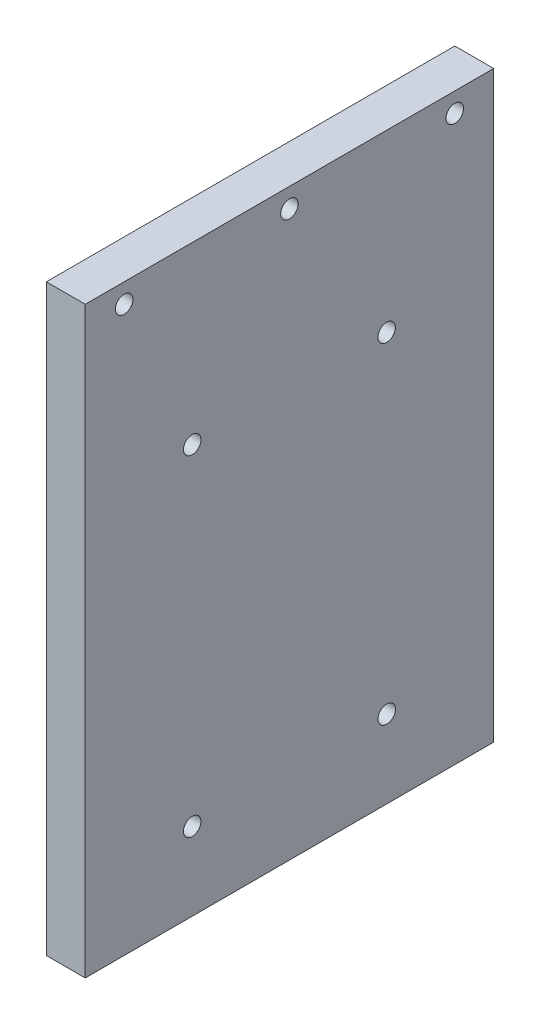
SolidWorks part; units mm, degrees
material "ABS"
ref_plane "Alzado" through (0, 0, 0) normal (0, 0, 1) x (1, 0, 0)
ref_plane "Planta" through (0, 0, 0) normal (0, 1, 0) x (1, 0, 0)
ref_plane "Vista lateral" through (0, 0, 0) normal (1, 0, 0) x (0, 0, -1)
sketch "Croquis1" plane through (0, 0, 0) normal (1, 0, 0) x (0, 0, -1)
  line L1 (-52.5, -75) -> (52.5, -75)
  line L2 (-52.5, -75) -> (-52.5, 75)
  line L3 (-52.5, 75) -> (52.5, 75)
  line L4 (52.5, -75) -> (52.5, 75)
  line L5 (-52.5, -75) -> (52.5, 75) construction
  line L6 (-52.5, 75) -> (52.5, -75) construction
  point P0 (0, 0)
  dimension "D1" = 105
  dimension "D2" = 150
extrude "Saliente-Extruir1" add sketch "Croquis1" along normal blind 10
sketch "Croquis2" plane through (10, 0, 0) normal (1, 0, 0) x (0, 0, -1)
  line L0 (0, 75) -> (0, 70) construction
  line L1 (52.5, 75) -> (-52.5, 75) construction
  line L2 (42.5, 70) -> (-42.5, 70) construction
  line L3 (-52.5, 75) -> (-52.5, -75) construction
  circle A0 centre (-42.5, 70) radius 2.25
  circle A1 centre (0, 70) radius 2.25
  circle A2 centre (42.5, 70) radius 2.25
  point P8 (0, 70)
  dimension "D3" = 4.5
  dimension "D1" = 10
  dimension "D2" = 5
extrude "Cortar-Extruir1" cut sketch "Croquis2" against normal through all
sketch "Croquis3" plane through (10, 0, 0) normal (1, 0, 0) x (0, 0, -1)
  line L0 (0, 75) -> (0, 30) construction
  line L1 (52.5, 75) -> (-52.5, 75) construction
  line L2 (25, 30) -> (-25, 30) construction
  line L4 (0, -75) -> (0, -55) construction
  line L5 (-52.5, -75) -> (52.5, -75) construction
  line L6 (25, -55) -> (-25, -55) construction
  circle A0 centre (25, 30) radius 2.25
  circle A1 centre (-25, 30) radius 2.25
  circle A4 centre (25, -55) radius 2.25
  circle A5 centre (-25, -55) radius 2.25
  point P8 (0, 30)
  point P17 (0, -55)
  dimension "D3" = 4.5
  dimension "D1" = 50
  dimension "D2" = 45
  dimension "D4" = 20
extrude "Cortar-Extruir2" cut sketch "Croquis3" against normal through all
